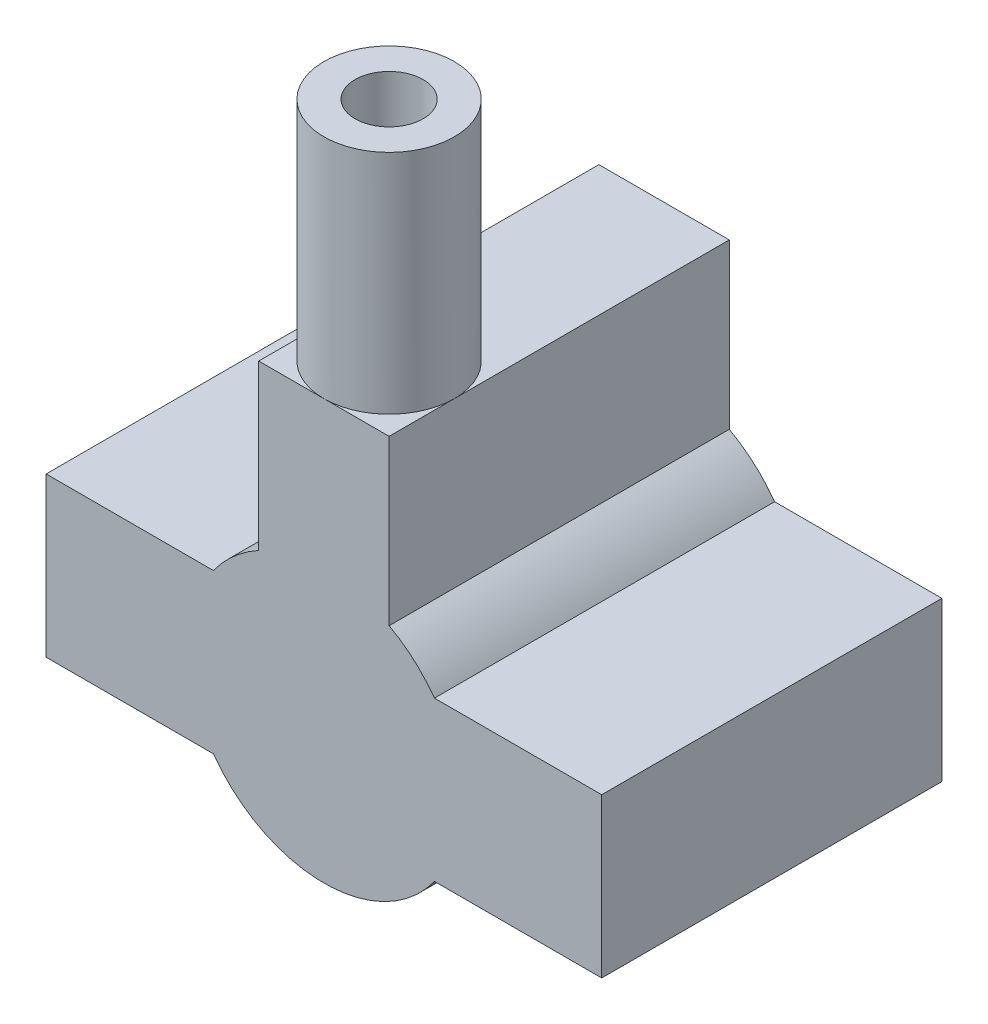
SolidWorks part; units mm, degrees
ref_plane "Front Plane" through (0, 0, 0) normal (0, 0, 1) x (1, 0, 0)
ref_plane "Top Plane" through (0, 0, 0) normal (0, 1, 0) x (1, 0, 0)
ref_plane "Right Plane" through (0, 0, 0) normal (1, 0, 0) x (0, 0, -1)
sketch "Sketch2" plane through (0, 0, 0) normal (0, 0, 1) x (1, 0, 0)
  line L0 (-131, -5) -> (-133.5, -5)
  line L1 (-131.1, -5) -> (-131.1, -7.8935)
  line L2 (-130.3006, -8.6) -> (-127.35, -8.6)
  line L3 (-127.35, -8.6) -> (-127.35, -11.4)
  line L4 (-127.35, -11.4) -> (-130.3006, -11.4)
  line L5 (-134.1994, -11.4) -> (-137.15, -11.4)
  line L6 (-137.15, -11.4) -> (-137.15, -8.6)
  line L7 (-137.15, -8.6) -> (-134.1994, -8.6)
  line L8 (-133.4, -7.8935) -> (-133.4, -5)
  line L26 (-133.5, -7.8349) -> (-133.5, -5)
  line L27 (-133.5, -5) -> (-138.75, -5)
  line L28 (-138.75, -5) -> (-138.75, -15)
  line L29 (-138.75, -15) -> (-125.75, -15)
  line L30 (-125.75, -15) -> (-125.75, -5)
  line L31 (-125.75, -5) -> (-131, -5)
  line L32 (-131, -5) -> (-131, -7.8349)
  line L33 (-130.25, -8.5) -> (-127.25, -8.5)
  line L34 (-127.25, -8.5) -> (-127.25, -11.5)
  line L35 (-127.25, -11.5) -> (-130.25, -11.5)
  line L36 (-134.25, -11.5) -> (-137.25, -11.5)
  line L37 (-137.25, -11.5) -> (-137.25, -8.5)
  line L38 (-137.25, -8.5) -> (-134.25, -8.5)
  arc A0 (-130.3006, -8.6) -> (-131.1, -7.8935) centre (-132.25, -10) ccw
  arc A1 (-134.1994, -11.4) -> (-130.3006, -11.4) centre (-132.25, -10) ccw
  arc A2 (-133.4, -7.8935) -> (-134.1994, -8.6) centre (-132.25, -10) ccw
  arc A6 (-133.5, -7.8349) -> (-134.25, -8.5) centre (-132.25, -10) ccw
  arc A7 (-130.25, -8.5) -> (-131, -7.8349) centre (-132.25, -10) ccw
  arc A8 (-134.25, -11.5) -> (-130.25, -11.5) centre (-132.25, -10) ccw
  dimension "D2" = 0.1
extrude "Boss-Extrude1" add sketch "Sketch2" against normal blind 6 contours L8 A2 L7 L6 L5 A1 L4 L3 L2 A0 L1 L0
sketch "Sketch3" plane through (0, -5, 0) normal (0, 1, 0) x (1, 0, 0)
  line L0 (-131.1, 1.15) -> (-133.4, 1.15)
  line L1 (-131.1, 6) -> (-131.1, 0) construction
  line L2 (-133.4, 6) -> (-133.4, 0) construction
  line L3 (-131.1, 0) -> (-133.4, 0) construction
  circle A0 centre (-132.25, 1.15) radius 1.15
extrude "Boss-Extrude2" add sketch "Sketch3" along normal offset from surface (4 mm away) 1 contours A0 L0 | L0 A0
sketch "Sketch4" plane through (0, -1, 0) normal (0, 1, 0) x (1, 0, 0)
  point P0 (-132.25, 1.15)
hole_wizard "M1.2x0.25 Tapped Hole1" positions "3DSketch1" profile "Sketch5" tap size "M1.2x0.25" standard "ANSI Metric"
sketch3d "3DSketch1"
  point P0 (-132.25, -1, -1.15)
sketch "Sketch5" plane through (-132.25, -1, -1.15) normal (1, 0, 0) x (0, 0, 1)
  line L0 (0, 0) -> (0, 3.4354)
  line L1 (0, 3.4354) -> (0.475, 3.15)
  line L2 (0.475, 3.15) -> (0.475, 2.4)
  line L3 (0.475, 2.4) -> (0.6, 2.4)
  line L4 (0.6, 2.4) -> (0.6, 0)
  line L5 (0.6, 0) -> (0, 0)
  line L10 (0, 3.4354) -> (-0.475, 3.15) construction
  line L11 (0, -6.35) -> (0, 107.95) construction
  dimension "Tap Drill Dia." = 0.95
  dimension "Tap Drill Depth" = 3.15
  dimension "Thread Major Dia." = 1.2
  dimension "Thread Depth" = 2.4
  dimension "Drill Angle" = 118
